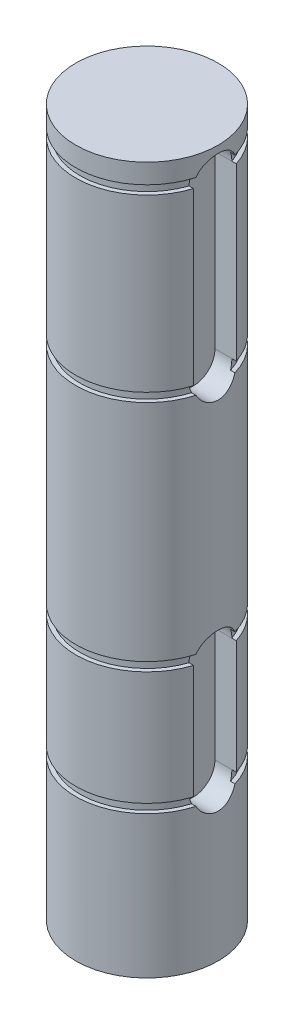
SolidWorks part; units mm, degrees
ref_plane "Front Plane" through (0, 0, 0) normal (0, 0, 1) x (1, 0, 0)
ref_plane "Top Plane" through (0, 0, 0) normal (0, 1, 0) x (1, 0, 0)
ref_plane "Right Plane" through (0, 0, 0) normal (1, 0, 0) x (0, 0, -1)
sketch "Sketch1" plane through (0, 0, 0) normal (0, 1, 0) x (1, 0, 0)
  circle A0 centre (0, 0) radius 3.125
extrude "Boss-Extrude1" add sketch "Sketch1" along normal blind 31.02 contours A0
sketch "Sketch2" plane through (0, 0, 0) normal (1, 0, 0) x (0, 0, -1)
  line L0 (-3.125, 0) -> (3.125, 0) construction
  line L1 (-6.8451, 6.64) -> (-2.94, 6.64)
  line L2 (-6.8451, 6.64) -> (-6.8451, 6.25)
  line L3 (-6.8451, 6.25) -> (-2.94, 6.25)
  line L4 (-2.94, 6.64) -> (-2.94, 6.25)
  line L5 (-3.125, 31.02) -> (-3.125, 0) construction
  line L6 (0, 10.0729) -> (0, 3.0392) construction
  dimension "D1" = 6.25
  dimension "D2" = 0.39
  dimension "D3" = 0.185
revolve "Cut-Revolve1" cut sketch "Sketch2" angle 360 about L6
sketch "Sketch3" plane through (0, 0, 0) normal (1, 0, 0) x (0, 0, -1)
  line L0 (-2.94, 6.64) -> (2.94, 6.64) construction
  line L1 (-6.6989, 12.03) -> (-2.94, 12.03)
  line L2 (-6.6989, 12.03) -> (-6.6989, 11.64)
  line L3 (-6.6989, 11.64) -> (-2.94, 11.64)
  line L4 (-2.94, 12.03) -> (-2.94, 11.64)
  line L5 (-3.125, 31.02) -> (-3.125, 6.64) construction
  line L6 (0, 13.6867) -> (0, 9.6026) construction
  dimension "D1" = 5
  dimension "D2" = 0.39
  dimension "D3" = 0.185
revolve "Cut-Revolve2" cut sketch "Sketch3" angle 360 about L6
sketch "Sketch4" plane through (0, 0, 0) normal (1, 0, 0) x (0, 0, -1)
  line L0 (-2.94, 12.03) -> (2.94, 12.03) construction
  line L1 (-12.2649, 22.27) -> (-2.94, 22.27)
  line L2 (-12.2649, 22.27) -> (-12.2649, 21.88)
  line L3 (-12.2649, 21.88) -> (-2.94, 21.88)
  line L4 (-2.94, 22.27) -> (-2.94, 21.88)
  line L5 (-3.125, 31.02) -> (-3.125, 12.03) construction
  line L6 (0, 25.015) -> (0, 20.3679) construction
  dimension "D1" = 9.85
  dimension "D2" = 0.39
  dimension "D3" = 0.185
revolve "Cut-Revolve3" cut sketch "Sketch4" angle 360 about L6
sketch "Sketch5" plane through (0, 0, 0) normal (1, 0, 0) x (0, 0, -1)
  line L0 (-2.94, 22.27) -> (2.94, 22.27) construction
  line L1 (-8.2591, 30.16) -> (-2.94, 30.16)
  line L2 (-8.2591, 30.16) -> (-8.2591, 29.77)
  line L3 (-8.2591, 29.77) -> (-2.94, 29.77)
  line L4 (-2.94, 30.16) -> (-2.94, 29.77)
  line L5 (-3.125, 31.02) -> (-3.125, 22.27) construction
  line L6 (0, 30.7138) -> (0, 26.722) construction
  dimension "D1" = 7.5
  dimension "D2" = 0.39
  dimension "D3" = 0.185
revolve "Cut-Revolve4" cut sketch "Sketch5" angle 360 about L6
ref_plane "Plane1" through (3.125, 0, 0) normal (1, 0, 0) x (0, 0, -1)
sketch "Sketch6" plane through (3.125, 0, 0) normal (1, 0, 0) x (0, 0, -1)
  line L0 (0, 29.77) -> (0, 22.27) construction
  line L1 (3.125, 29.77) -> (-3.125, 29.77) construction
  line L2 (-2.94, 22.27) -> (2.94, 22.27) construction
  line L3 (0.94, 29.77) -> (0.94, 22.27)
  line L4 (-0.94, 29.77) -> (-0.94, 22.27)
  arc A0 (0.94, 29.77) -> (-0.94, 29.77) centre (0, 29.77) ccw
  arc A1 (-0.94, 22.27) -> (0.94, 22.27) centre (0, 22.27) ccw
  point P6 (0, 26.02)
extrude "Cut-Extrude1" cut sketch "Sketch6" against normal blind 1.08 contours L4 A1 L3 A0
sketch "Sketch7" plane through (3.125, 0, 0) normal (1, 0, 0) x (0, 0, -1)
  line L0 (0, 11.64) -> (0, 6.64) construction
  line L1 (3.125, 11.64) -> (-3.125, 11.64) construction
  line L2 (-2.94, 6.64) -> (2.94, 6.64) construction
  line L3 (0.94, 11.64) -> (0.94, 6.64)
  line L4 (-0.94, 11.64) -> (-0.94, 6.64)
  arc A0 (0.94, 11.64) -> (-0.94, 11.64) centre (0, 11.64) ccw
  arc A1 (-0.94, 6.64) -> (0.94, 6.64) centre (0, 6.64) ccw
  point P6 (0, 9.14)
extrude "Cut-Extrude2" cut sketch "Sketch7" against normal blind 1.08 contours L4 A1 L3 A0
